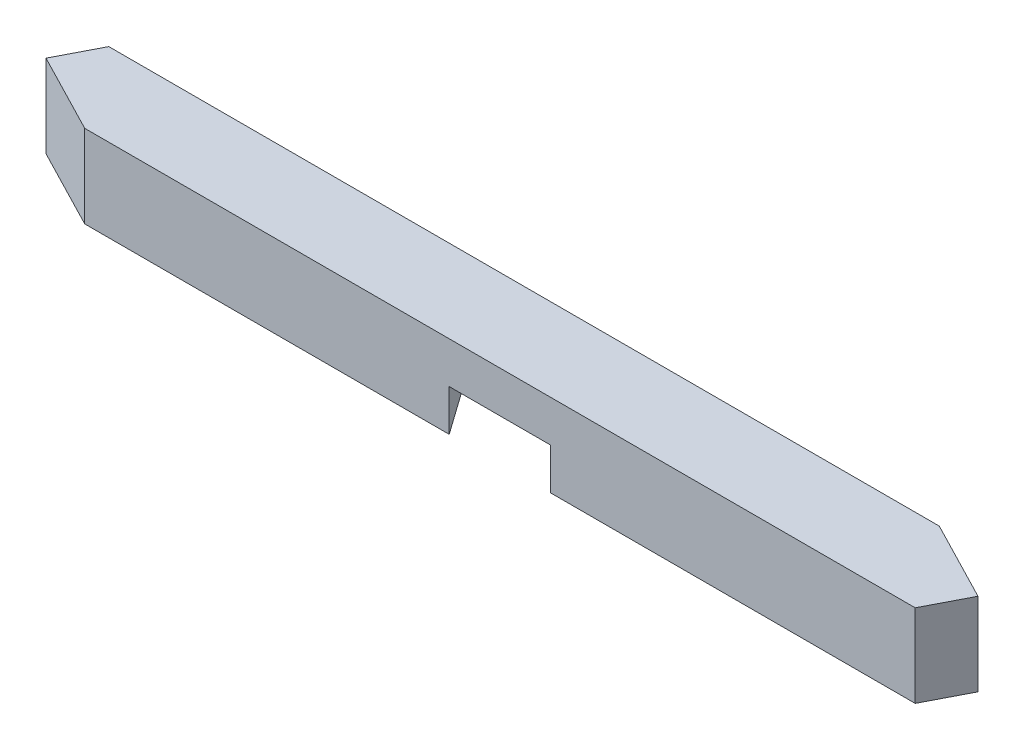
SolidWorks part; units mm, degrees
ref_plane "Front Plane" through (0, 0, 0) normal (0, 0, 1) x (1, 0, 0)
ref_plane "Top Plane" through (0, 0, 0) normal (0, 1, 0) x (1, 0, 0)
ref_plane "Right Plane" through (0, 0, 0) normal (1, 0, 0) x (0, 0, -1)
sketch "Sketch1" plane through (0, 0, 0) normal (0, 1, 0) x (1, 0, 0)
  line L0 (0, 0) -> (214.4242, 0) construction
  line L1 (45.179, 87.4433) -> (169.2451, -87.4433) construction
  line L2 (45.179, 87.4433) -> (0, 0) construction
  line L3 (45.179, 87.4433) -> (214.4242, 0) construction
  line L4 (214.4242, 0) -> (169.2451, -87.4433) construction
  line L5 (169.2451, -87.4433) -> (0, 0) construction
  line L6 (0, 0) -> (4.9213, 9.525)
  line L7 (4.9213, 9.525) -> (195.9887, 9.525)
  line L8 (195.9887, 9.525) -> (214.4242, 0)
  line L9 (214.4242, 0) -> (209.5029, -9.525)
  line L10 (209.5029, -9.525) -> (18.4355, -9.525)
  line L11 (18.4355, -9.525) -> (0, 0)
  point P5 (107.2121, 0)
  point P6 (107.2121, 0)
  dimension "D1" = 214.4242
  dimension "D2" = 214.4242
  dimension "D3" = 98.425
  dimension "D4" = 19.05
  dimension "D5" = 9.525
  dimension "D6" = 190.5
extrude "Boss-Extrude1" add sketch "Sketch1" along normal blind 19.05
sketch "Sketch3" plane through (0, 0, 0) normal (0, 1, 0) x (1, 0, 0)
  line L0 (0, 0) -> (214.4242, 0) construction
  line L1 (45.179, 87.4433) -> (169.2451, -87.4433) construction
  line L2 (45.179, 87.4433) -> (0, 0) construction
  line L3 (45.179, 87.4433) -> (214.4242, 0) construction
  line L4 (214.4242, 0) -> (169.2451, -87.4433) construction
  line L5 (169.2451, -87.4433) -> (0, 0) construction
  line L6 (45.179, 87.4433) -> (40.2578, 77.9183)
  line L7 (40.2578, 77.9183) -> (150.8097, -77.9183)
  line L8 (150.8097, -77.9183) -> (169.2451, -87.4433)
  line L9 (169.2451, -87.4433) -> (174.1664, -77.9183)
  line L10 (174.1664, -77.9183) -> (63.6145, 77.9183)
  line L11 (63.6145, 77.9183) -> (45.179, 87.4433)
  point P5 (107.2121, 0)
  point P6 (107.2121, 0)
  dimension "D1" = 214.4242
  dimension "D2" = 214.4242
  dimension "D3" = 98.425
  dimension "D4" = 19.05
  dimension "D5" = 9.525
extrude "Cut-Extrude1" cut sketch "Sketch3" along normal blind 9.525
